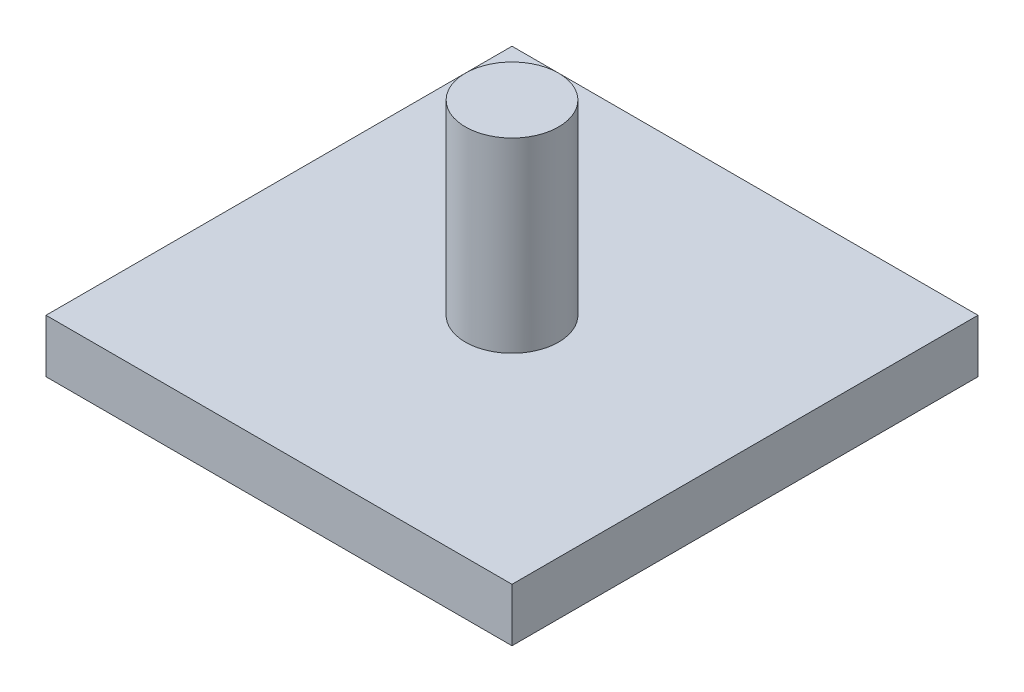
SolidWorks part; units mm, degrees
ref_plane "Front Plane" through (0, 0, 0) normal (0, 0, 1) x (1, 0, 0)
ref_plane "Top Plane" through (0, 0, 0) normal (0, 1, 0) x (1, 0, 0)
ref_plane "Right Plane" through (0, 0, 0) normal (1, 0, 0) x (0, 0, -1)
sketch "Sketch1" plane through (0, 0, 0) normal (0, 1, 0) x (1, 0, 0)
  line L1 (-35, 35) -> (35, 35)
  line L2 (-35, 35) -> (-35, -35)
  line L3 (-35, -35) -> (35, -35)
  line L4 (35, 35) -> (35, -35)
  line L5 (-35, 35) -> (35, -35) construction
  line L6 (-35, -35) -> (35, 35) construction
  point P0 (0, 0)
  dimension "D1" = 70
  dimension "D2" = 70
extrude "Boss-Extrude1" add sketch "Sketch1" along normal blind 8
sketch "Sketch3" plane through (0, 0, 0) normal (0, 0, 1) x (1, 0, 0)
  line L0 (0, 0) -> (-7, 0)
  line L1 (-35, 0) -> (35, 0) construction
  line L2 (-7, 0) -> (-7, 36)
  line L3 (-7, 36) -> (0, 36)
  line L4 (0, 36) -> (0, 0)
  line L5 (0, -7.2633) -> (0, 40.7281) construction
  dimension "D1" = 36
  dimension "D2" = 7
revolve "Revolve1" add sketch "Sketch3" angle 360 about L5
sketch "Sketch4" plane through (0, 0, 0) normal (0, 0, 1) x (1, 0, 0)
  line L0 (0, 0) -> (0, 60.0213) construction
  line L1 (0, 60.0213) -> (0, 36.0213) construction
  line L2 (0, 36.0213) -> (-24.4854, 36.0213) construction
  line L3 (-24.4854, 36.0213) -> (21.9389, 36.0213) construction
  circle A0 centre (0, 60.0213) radius 24
  circle A1 centre (0, 60.0213) radius 17
  dimension "D2" = 48
  dimension "D3" = 34
  dimension "D1" = 24
